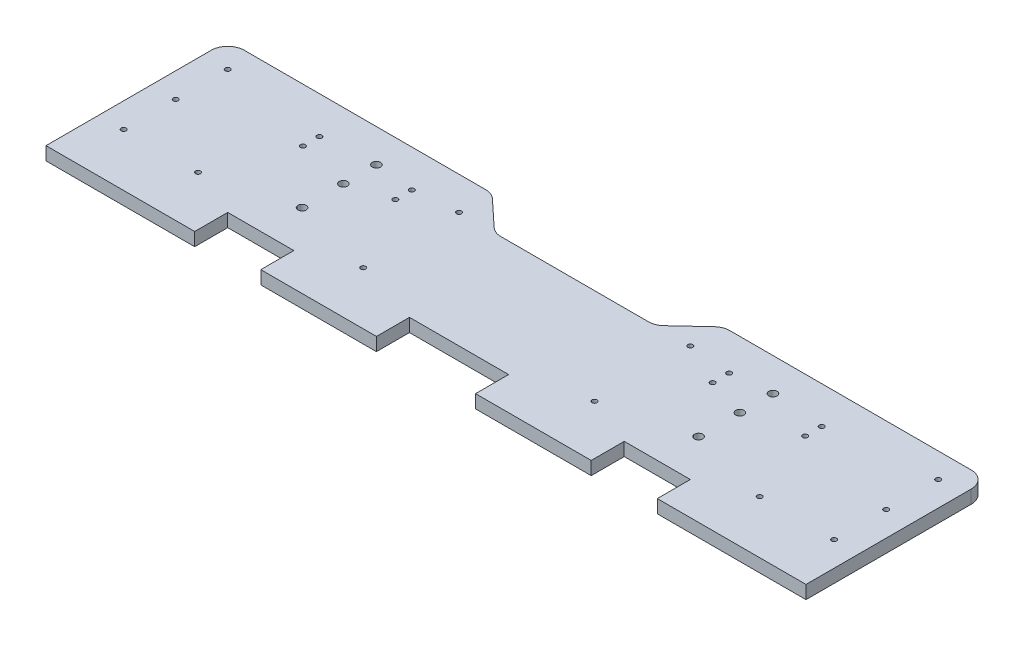
SolidWorks part; units mm, degrees
ref_plane "前视基准面" through (0, 0, 0) normal (0, 0, 1) x (1, 0, 0)
ref_plane "上视基准面" through (0, 0, 0) normal (0, 1, 0) x (1, 0, 0)
ref_plane "右视基准面" through (0, 0, 0) normal (1, 0, 0) x (0, 0, -1)
sketch "草图2" plane through (0, 0, 0) normal (0, 1, 0) x (1, 0, 0)
  line L1 (-230, 55) -> (230, 55)
  line L2 (-230, 55) -> (-230, -55)
  line L3 (-230, -55) -> (230, -55)
  line L4 (230, 55) -> (230, -55)
  line L5 (-230, 55) -> (230, -55) construction
  line L6 (-230, -55) -> (230, 55) construction
  point P0 (0, 0)
  dimension "D1" = 460
  dimension "D2" = 110
extrude "凸台-拉伸1" add sketch "草图2" along normal blind 8
sketch "草图3" plane through (0, 8, 0) normal (0, 1, 0) x (1, 0, 0)
  line L0 (-70, 55) -> (-48.5526, 35)
  line L1 (230, 55) -> (-230, 55) construction
  line L2 (-48.5526, 35) -> (48.5526, 35)
  line L3 (48.5526, 35) -> (70, 55)
  line L4 (70, 55) -> (-70, 55)
  line L5 (-230, 55) -> (-230, -55) construction
  circle A0 centre (-120, 35) radius 2.5
  circle A2 centre (-120, 15) radius 2.5
  circle A3 centre (-152, 32.5) radius 1.5
  circle A4 centre (-152, 22.5) radius 1.5
  circle A5 centre (-96, 32.5) radius 1.5
  circle A6 centre (-96, 22.5) radius 1.5
  circle A7 centre (-120, -10) radius 2.5
  dimension "D6" = 110
  dimension "D9" = 78
  dimension "D12" = 24
  dimension "D13" = 25
  dimension "D1" = 20
  dimension "D2" = 43
  dimension "D3" = 43
  dimension "D4" = 160
  dimension "D5" = 160
  dimension "D7" = 20
  dimension "D8" = 20
  dimension "D10" = 22.5
  dimension "D11" = 10
sketch "草图4" plane through (0, 8, 0) normal (0, 1, 0) x (1, 0, 0)
  line L0 (-230, -55) -> (230, -55) construction
  line L1 (230, 55) -> (-230, 55) construction
  line L3 (-230, 55) -> (-230, -55) construction
  circle A0 centre (-70, 35) radius 1.5
  circle A1 centre (-70, -23) radius 1.5
  circle A2 centre (-215, -23) radius 1.5
  circle A3 centre (-215, 40) radius 1.5
  circle A5 centre (-170, -23) radius 1.5
  circle A6 centre (-215, 8.5) radius 1.5
  dimension "D1" = 32
  dimension "D2" = 15
  dimension "D3" = 15
  dimension "D4" = 31.5
  dimension "D5" = 20
  dimension "D6" = 160
  dimension "D7" = 45
extrude "切除-拉伸1" cut sketch "草图4" against normal through all
extrude "切除-拉伸2" cut sketch "草图3" against normal through all
mirror "镜向1" about plane through (0, 0, 0) normal (1, 0, 0) of "切除-拉伸1", "切除-拉伸2"
fillet "圆角1" radius 10 6 edges at (-230, 4, -55) (230, 4, -55) (70, 4, -55) (48.5526, 4, -35) (-48.5526, 4, -35) (-70, 4, -55)
sketch "草图5" plane through (0, 8, 0) normal (0, 1, 0) x (1, 0, 0)
  line L1 (-30, -55) -> (30, -55)
  line L2 (-30, -55) -> (-30, -35)
  line L3 (-30, -35) -> (30, -35)
  line L4 (30, -55) -> (30, -35)
  line L5 (-30, -55) -> (30, -35) construction
  line L6 (-30, -35) -> (30, -55) construction
  line L8 (100, -55) -> (140, -55)
  line L9 (100, -55) -> (100, -35)
  line L10 (100, -35) -> (140, -35)
  line L11 (140, -55) -> (140, -35)
  line L12 (100, -55) -> (140, -35) construction
  line L13 (100, -35) -> (140, -55) construction
  line L14 (-230, -55) -> (230, -55) construction
  line L15 (0, -4.4) -> (0, 4.4) construction
  line L16 (230, -55) -> (230, 45) construction
  point P6 (0, -45)
  point P7 (92.6989, -55)
  point P16 (120, -45)
  dimension "D1" = 60
  dimension "D2" = 40
  dimension "D3" = 20
  dimension "D4" = 110
extrude "切除-拉伸3" cut sketch "草图5" against normal through all
mirror "镜向2" about plane through (0, 0, 0) normal (1, 0, 0) of "切除-拉伸3"
